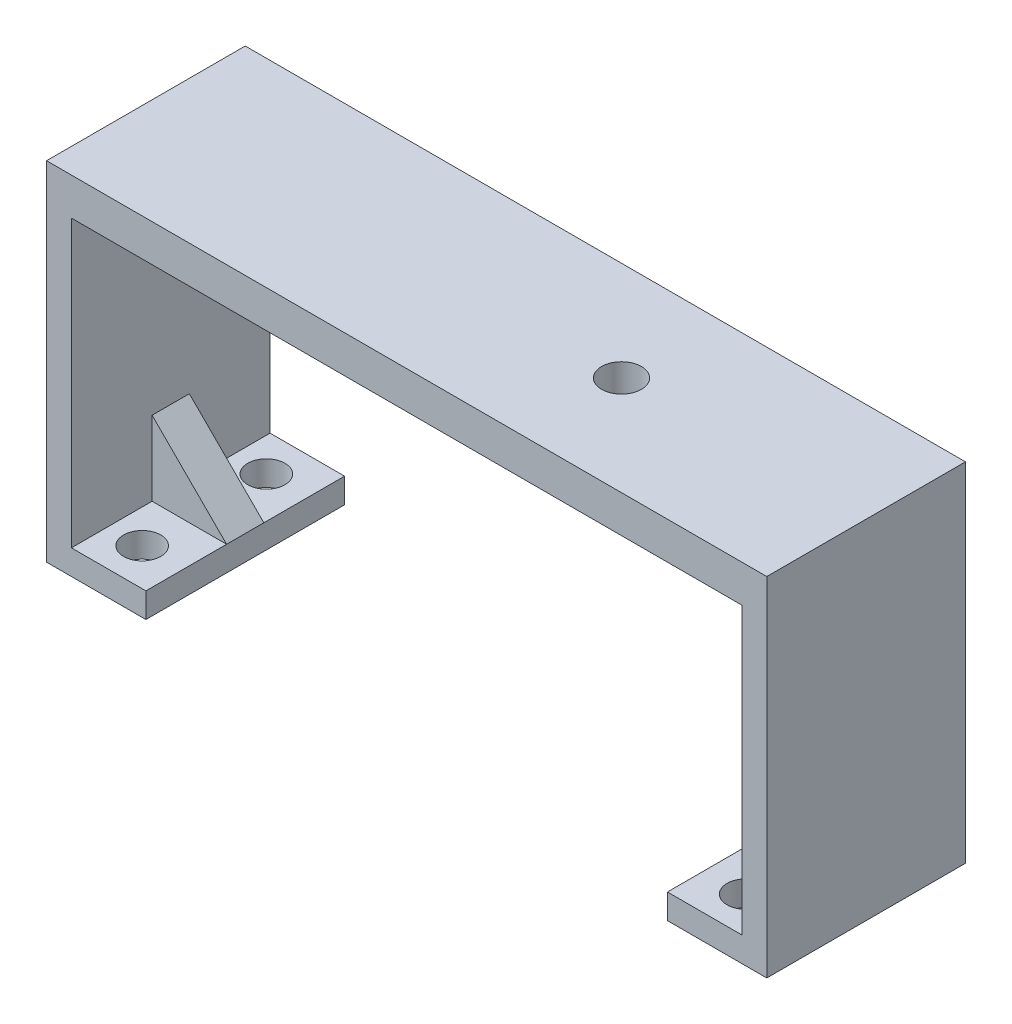
SolidWorks part; units mm, degrees
ref_plane "Plano frontal" through (0, 0, 0) normal (0, 0, 1) x (1, 0, 0)
ref_plane "Plano superior" through (0, 0, 0) normal (0, 1, 0) x (1, 0, 0)
ref_plane "Plano direito" through (0, 0, 0) normal (1, 0, 0) x (0, 0, -1)
sketch "Esboço1" plane through (0, 0, 0) normal (0, 0, 1) x (1, 0, 0)
  line L0 (-21, 0) -> (-29, 0)
  line L1 (-27, 2) -> (-27, 25)
  line L2 (-27, 25) -> (27, 25)
  line L3 (21, 2) -> (21, 0)
  line L4 (27, 2) -> (21, 2)
  line L5 (29, 28) -> (29, 0)
  line L6 (27, 2) -> (27, 25)
  line L7 (21, 0) -> (29, 0)
  line L8 (29, 28) -> (-29, 28)
  line L9 (-29, 28) -> (-29, 0)
  line L10 (-27, 2) -> (-21, 2)
  line L11 (-21, 2) -> (-21, 0)
  line L12 (0, 0) -> (0, 33.1059) construction
  point P14 (0, 28)
  point P16 (0, 25)
  dimension "D1" = 3
  dimension "D2" = 2
  dimension "D3" = 42
  dimension "D4" = 28
  dimension "D5" = 2
  dimension "D6" = 6
extrude "Ressalto-extrusão1" add sketch "Esboço1" along normal mid plane 16
sketch "Esboço2" plane through (0, 0, 0) normal (0, -1, 0) x (1, 0, 0)
  line L0 (0, 0) -> (0, 8) construction
  line L1 (-24.3, 5) -> (-24.3, -5) construction
  line L2 (-29, 8) -> (-29, -8) construction
  line L3 (24.3, 5) -> (24.3, -5) construction
  line L4 (-27, 8) -> (27, 8) construction
  circle A0 centre (-24.3, -5) radius 1.5
  circle A1 centre (-24.3, 5) radius 1.5
  circle A2 centre (24.3, 5) radius 1.5
  circle A3 centre (24.3, -5) radius 1.5
  point P7 (-24.3, 0)
  point P10 (-29, 0)
  dimension "D2" = 3
  dimension "D3" = 48.6
  dimension "D1" = 10
extrude "Corte-extrusão1" cut sketch "Esboço2" against normal blind 16
sketch "Esboço4" plane through (0, 0, 0) normal (0, 0, 1) x (1, 0, 0)
  line L0 (-21, 2) -> (-27, 8)
  line L1 (-27, 2) -> (-27, 25) construction
  line L2 (-27, 8) -> (-27, 2)
  line L3 (-27, 2) -> (-21, 2)
  line L4 (21, 2) -> (27, 2)
  line L5 (27, 2) -> (27, 8)
  line L6 (27, 25) -> (27, 2) construction
  line L7 (27, 8) -> (21, 2)
extrude "Ressalto-extrusão3" add sketch "Esboço4" along normal mid plane 3
sketch "Esboço6" plane through (0, 28, 0) normal (0, 1, 0) x (1, 0, 0)
  circle A0 centre (9.3, 0) radius 1.6
  circle A1 centre (24.3, -5) radius 1.5 construction
  dimension "D1" = 15
  dimension "D2" = 3.2
extrude "Corte-extrusão2" cut sketch "Esboço6" against normal blind 3
